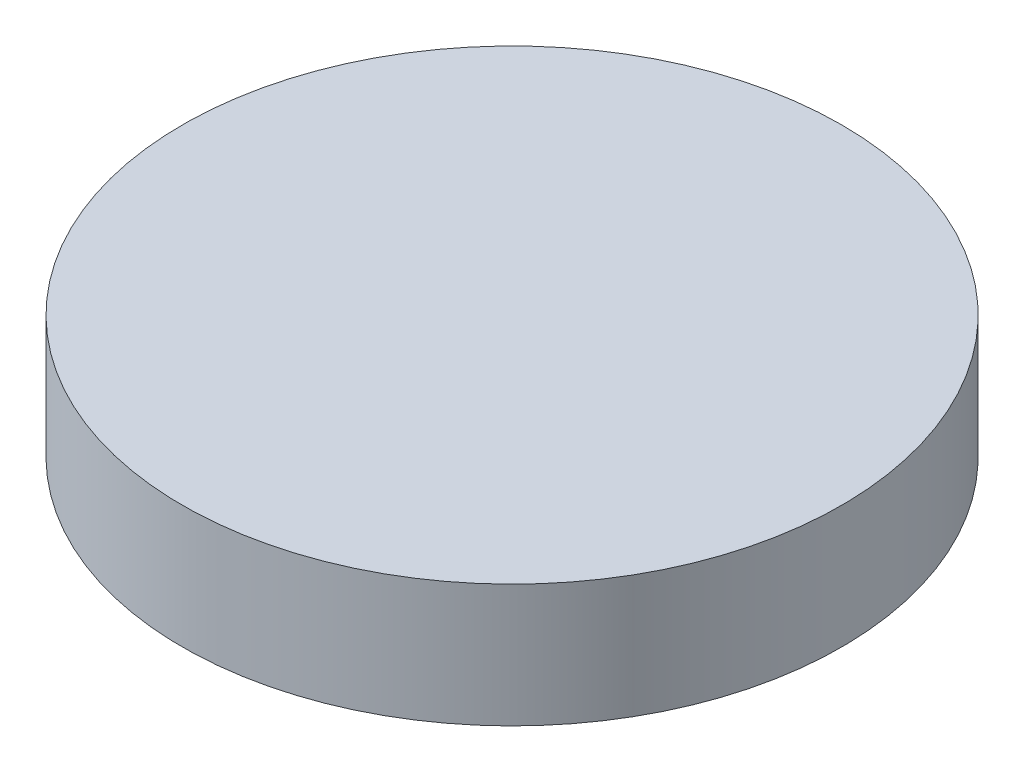
SolidWorks part; units mm, degrees
ref_plane "Front Plane" through (0, 0, 0) normal (0, 0, 1) x (1, 0, 0)
ref_plane "Top Plane" through (0, 0, 0) normal (0, 1, 0) x (1, 0, 0)
ref_plane "Right Plane" through (0, 0, 0) normal (1, 0, 0) x (0, 0, -1)
sketch "Sketch1" plane through (0, 0, 0) normal (0, 1, 0) x (1, 0, 0)
  circle A0 centre (0, 0) radius 51.1302
  dimension "D1" = 102.2604
extrude "Boss-Extrude1" add sketch "Sketch1" along normal blind 19.05
